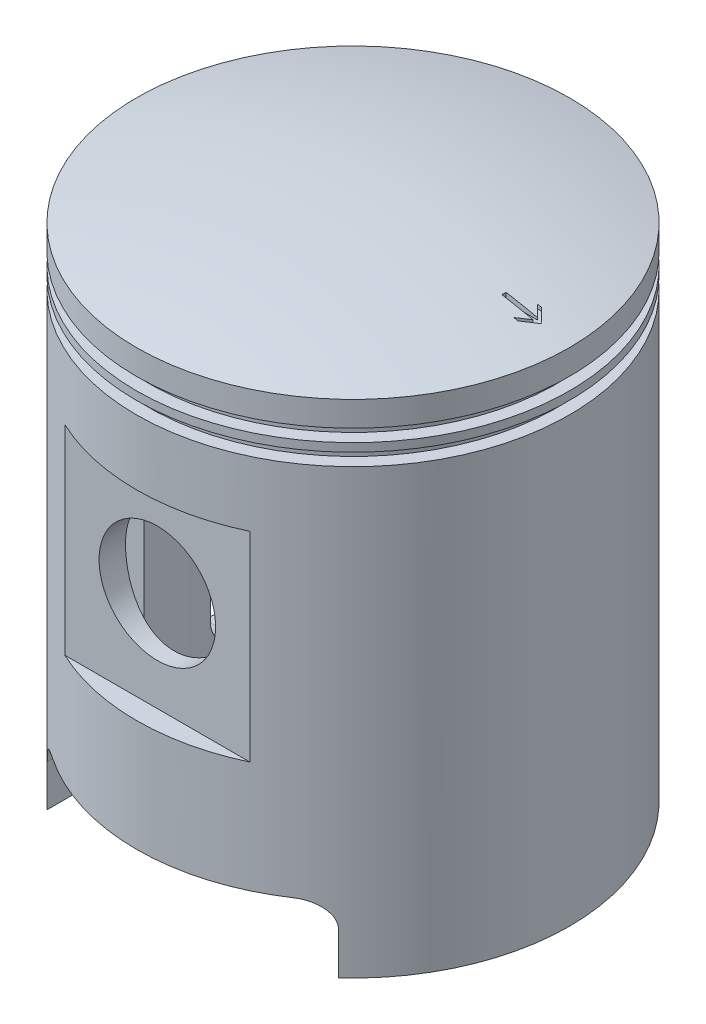
SolidWorks part; units mm, degrees
ref_plane "Спереди" through (0, 0, 0) normal (0, 0, 1) x (1, 0, 0)
ref_plane "Сверху" through (0, 0, 0) normal (0, 1, 0) x (1, 0, 0)
ref_plane "Справа" through (0, 0, 0) normal (1, 0, 0) x (0, 0, -1)
sketch "Эскиз1" plane through (0, 0, 0) normal (0, 1, 0) x (1, 0, 0)
  circle A0 centre (0, 0) radius 26
  dimension "D1" = 52
extrude "Бобышка-Вытянуть1" add sketch "Эскиз1" along normal blind 60.2
sketch "Эскиз2" plane through (0, 0, 0) normal (0, 0, 1) x (1, 0, 0)
  line L0 (0, 60.2) -> (0, 63.5) construction
  line L1 (26, 60.2) -> (-26, 60.2) construction
  line L2 (26, 60.2) -> (0, 60.2)
  line L3 (0, 60.2) -> (0, 63.5)
  arc A0 (0, 63.5) -> (26, 60.2) centre (0, -40.5742) cw
  dimension "D1" = 3.3
revolve "Повернуть1" add sketch "Эскиз2" angle 360 about L0
sketch "Эскиз3" plane through (0, 0, 0) normal (0, 0, 1) x (1, 0, 0)
  line L0 (17.5, 0) -> (-17.5, 0)
  line L1 (-26, 0) -> (26, 0) construction
  line L2 (0, 0) -> (0, 12.6131) construction
  line L3 (-17.5, 0) -> (-17.5, 5)
  line L4 (-14.5, 8) -> (14.5, 8)
  line L5 (17.5, 0) -> (17.5, 5)
  circle A0 centre (0, 33.4) radius 7
  arc A1 (-14.5, 8) -> (-17.5, 5) centre (-14.5, 5) ccw
  arc A2 (14.5, 8) -> (17.5, 5) centre (14.5, 5) cw
  point P13 (-17.5, 8)
  point P18 (0, 8)
  dimension "D1" = 14
  dimension "D5" = 3
  dimension "D2" = 26.8
  dimension "D3" = 17.5
  dimension "D4" = 8
extrude "Вырез-Вытянуть1" cut sketch "Эскиз3" against normal mid plane 60.2
sketch "Эскиз4" plane through (0, 0, 0) normal (0, 1, 0) x (1, 0, 0)
  circle A0 centre (0, 0) radius 21.5
  dimension "D1" = 43
extrude "Вырез-Вытянуть2" cut sketch "Эскиз4" along normal blind 51
sketch "Эскиз5" plane through (0, 0, 0) normal (0, 0, 1) x (1, 0, 0)
  line L0 (-26, 57.2) -> (-24.5, 57.2)
  line L1 (-26, 60.2) -> (-26, 0) construction
  line L2 (-24.5, 57.2) -> (-24.5, 55.7)
  line L3 (-24.5, 55.7) -> (-26, 55.7)
  line L5 (-26, 57.2) -> (-26, 55.7)
  line L6 (-24.5, 54.7) -> (-26, 54.7)
  line L7 (-24.5, 53.2) -> (-24.5, 54.7)
  line L8 (-26, 53.2) -> (-24.5, 53.2)
  line L9 (-26, 53.2) -> (-26, 54.7)
  line L10 (0, 37.0322) -> (0, 67.4951) construction
  dimension "D1" = 1.5
  dimension "D2" = 1.5
  dimension "D3" = 3
revolve "Вырез-Повернуть1" cut sketch "Эскиз5" angle 360 about L10
sketch "Эскиз6" plane through (0, 0, 0) normal (1, 0, 0) x (0, 0, -1)
  line L0 (0, 0) -> (0, 47.8055) construction
  line L1 (-4, 6) -> (-4, 25)
  line L2 (-7, 28) -> (-10, 28)
  line L3 (-13, 25) -> (-13, 6)
  line L4 (-10, 3) -> (-7, 3)
  line L5 (10, 3) -> (7, 3)
  line L6 (13, 25) -> (13, 6)
  line L7 (7, 28) -> (10, 28)
  line L8 (4, 6) -> (4, 25)
  arc A0 (-4, 6) -> (-7, 3) centre (-7, 6) cw
  arc A1 (-10, 3) -> (-13, 6) centre (-10, 6) cw
  arc A2 (-4, 25) -> (-7, 28) centre (-7, 25) ccw
  arc A3 (-13, 25) -> (-10, 28) centre (-10, 25) cw
  arc A4 (13, 25) -> (10, 28) centre (10, 25) ccw
  arc A5 (4, 25) -> (7, 28) centre (7, 25) cw
  arc A6 (10, 3) -> (13, 6) centre (10, 6) ccw
  arc A7 (4, 6) -> (7, 3) centre (7, 6) ccw
  point P9 (-4, 3)
  point P14 (-4, 28)
  point P17 (-13, 28)
  point P30 (13, 28)
  point P31 (4, 28)
  point P32 (4, 3)
  dimension "D5" = 3
  dimension "D1" = 25
  dimension "D2" = 4
  dimension "D3" = 3
  dimension "D4" = 9
extrude "Вырез-Вытянуть3" cut sketch "Эскиз6" against normal blind 50
sketch "Эскиз8" plane through (0, 0, 0) normal (0, 0, 1) x (1, 0, 0)
  point P0 (0, 33.4)
sketch "Эскиз9" plane through (0, 0, 0) normal (1, 0, 0) x (0, 0, -1)
  line L0 (-23.5043, 45.4) -> (-23.5043, 21.4)
  line L3 (-23.5043, 45.4) -> (-29.0043, 45.4)
  line L4 (-29.0043, 45.4) -> (-29.0043, 21.4)
  line L5 (-23.5043, 21.4) -> (-29.0043, 21.4)
  line L6 (0, 33.4) -> (0, 46.2599) construction
  line L7 (25.04, 33.4) -> (25.04, 43.1039) construction
  line L8 (23.5043, 21.4) -> (29.0043, 21.4)
  line L9 (29.0043, 45.4) -> (29.0043, 21.4)
  line L10 (23.5043, 45.4) -> (29.0043, 45.4)
  line L11 (23.5043, 21.4) -> (23.5043, 45.4)
  point P11 (-29.0043, 33.4)
  point P19 (29.0043, 33.4)
  dimension "D1" = 5.5
extrude "Вырез-Вытянуть4" cut sketch "Эскиз9" against normal mid plane 50
ref_plane "Плоскость1" through (0, 63, 0) normal (0, 1, 0) x (1, 0, 0)
sketch "Эскиз10" plane through (0, 63, 0) normal (0, 1, 0) x (1, 0, 0)
  line L0 (0, 0) -> (26, 0) construction
  line L1 (22.6415, 0) -> (21.2273, 1.4142)
  line L2 (21.2273, 1.4142) -> (20.7273, 1.4142)
  line L3 (18.1415, -0.25) -> (18.1415, 0.25)
  line L4 (18.1415, 0.25) -> (21.8915, 0.25)
  line L5 (20.7273, 1.4142) -> (21.8915, 0.25)
  line L6 (18.1415, -0.25) -> (21.8915, -0.25)
  line L7 (20.7273, -1.4142) -> (21.8915, -0.25)
  line L8 (21.2273, -1.4142) -> (20.7273, -1.4142)
  line L9 (22.6415, 0) -> (21.2273, -1.4142)
  circle A0 centre (0, 0) radius 26 construction
  point P12 (18.1415, 0)
  dimension "D1" = 2
  dimension "D2" = 0.5
  dimension "D3" = 0.25
  dimension "D4" = 4.5
extrude "Вырез-Вытянуть5" cut sketch "Эскиз10" against normal blind 2.1
